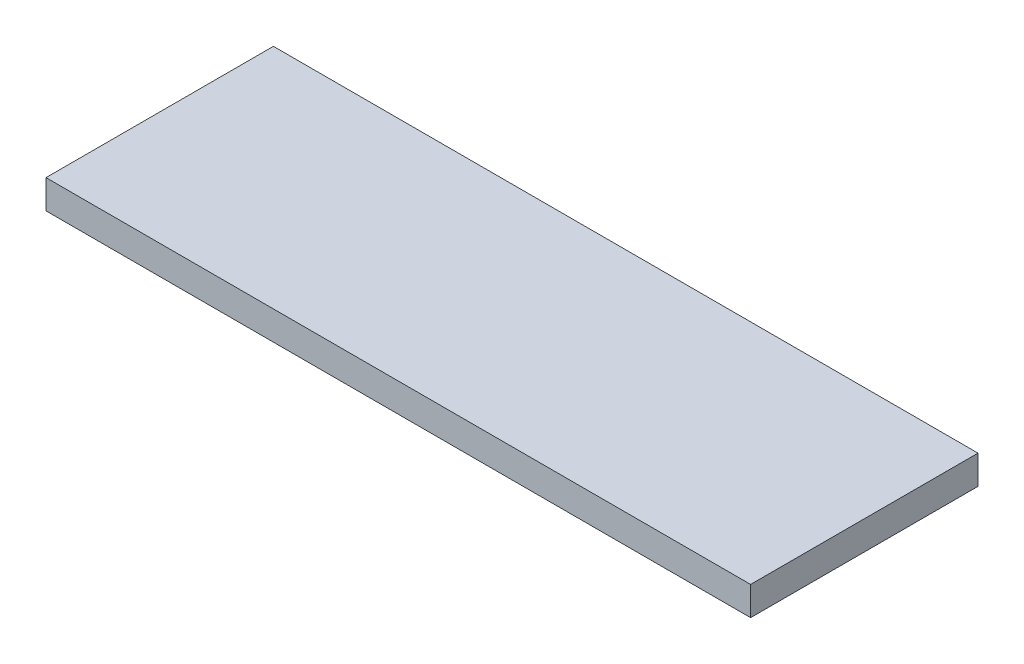
SolidWorks part; units mm, degrees
ref_plane "Alzado" through (0, 0, 0) normal (0, 0, 1) x (1, 0, 0)
ref_plane "Planta" through (0, 0, 0) normal (0, 1, 0) x (1, 0, 0)
ref_plane "Vista lateral" through (0, 0, 0) normal (1, 0, 0) x (0, 0, -1)
sketch "Croquis1" plane through (0, 0, 0) normal (0, 1, 0) x (1, 0, 0)
  line L1 (-209.6918, 60.9102) -> (255.0882, 60.9102)
  line L2 (-209.6918, 60.9102) -> (-209.6918, -89.0898)
  line L3 (-209.6918, -89.0898) -> (255.0882, -89.0898)
  line L4 (255.0882, 60.9102) -> (255.0882, -89.0898)
  dimension "D1" = 464.78
  dimension "D2" = 150
extrude "Saliente-Extruir1" add sketch "Croquis1" along normal blind 19
